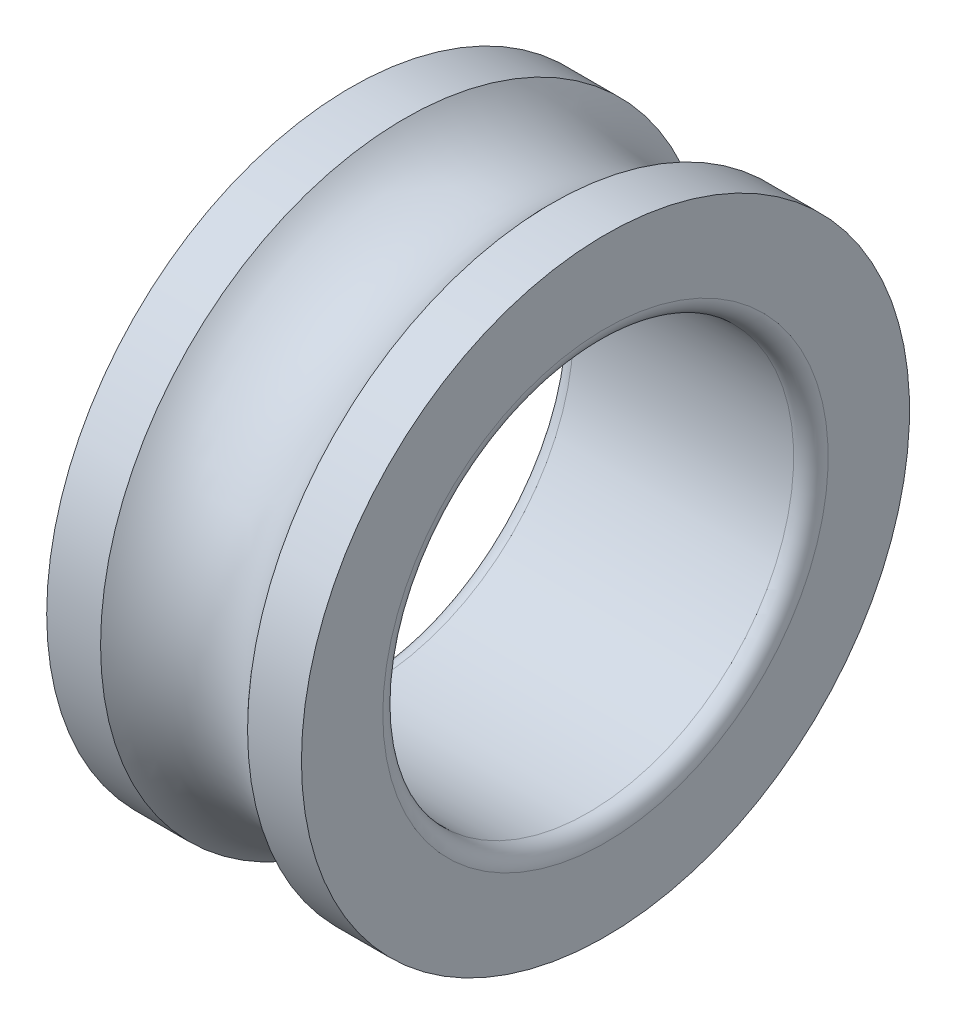
SolidWorks part; units mm, degrees
ref_plane "Front Plane" through (0, 0, 0) normal (0, 0, 1) x (1, 0, 0)
ref_plane "Top Plane" through (0, 0, 0) normal (0, 1, 0) x (1, 0, 0)
ref_plane "Right Plane" through (0, 0, 0) normal (1, 0, 0) x (0, 0, -1)
sketch "Sketch1" plane through (0, 0, 0) normal (0, 0, 1) x (1, 0, 0)
  line L0 (-29.9747, 0) -> (35.9429, 0) construction
  line L1 (-3.7439, 83.1007) -> (-3.7439, -9.1007) construction
  line L2 (-19.2439, 37) -> (-12.6882, 37)
  line L3 (-19.2439, 37) -> (-19.2439, 27.1)
  line L4 (-17.1439, 25) -> (9.6561, 25)
  line L5 (11.7561, 37) -> (11.7561, 27.1)
  line L6 (5.2004, 37) -> (11.7561, 37)
  arc A0 (5.2004, 37) -> (-12.6882, 37) centre (-3.7439, 45) cw
  arc A1 (9.6561, 25) -> (11.7561, 27.1) centre (9.6561, 27.1) ccw
  arc A2 (-19.2439, 27.1) -> (-17.1439, 25) centre (-17.1439, 27.1) ccw
  point P10 (-3.7439, 37)
  dimension "D5" = 12
  dimension "D6" = 2.1
  dimension "D1" = 31
  dimension "D2" = 25
  dimension "D3" = 37
  dimension "D4" = 8
revolve "Revolve1" add sketch "Sketch1" angle 360 about L0
scale "Scale1" scale about centroid uniform scaling yes scale factor 0.168
